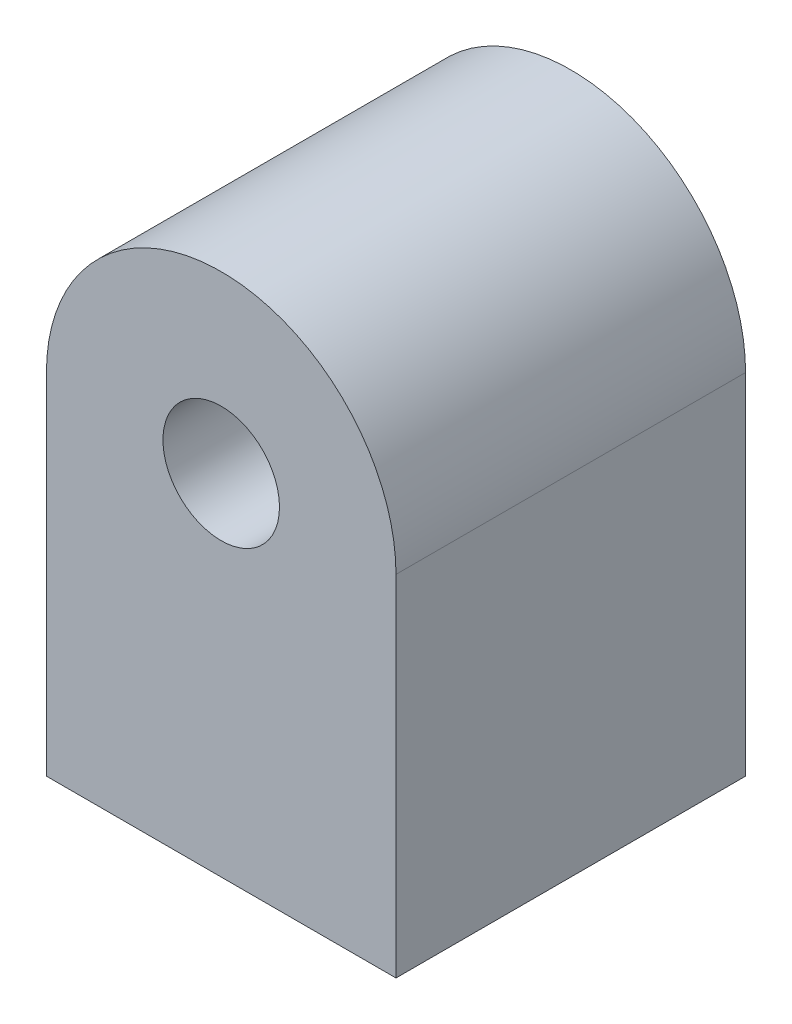
SolidWorks part; units mm, degrees
ref_plane "Front Plane" through (0, 0, 0) normal (0, 0, 1) x (1, 0, 0)
ref_plane "Top Plane" through (0, 0, 0) normal (0, 1, 0) x (1, 0, 0)
ref_plane "Right Plane" through (0, 0, 0) normal (1, 0, 0) x (0, 0, -1)
sketch "Sketch1" plane through (0, 0, 0) normal (0, 0, 1) x (1, 0, 0)
  line L0 (0, 0) -> (60, 0)
  line L1 (60, 0) -> (60, 60)
  line L2 (0, 60) -> (0, 0)
  arc A0 (60, 60) -> (0, 60) centre (30, 60) ccw
  circle A1 centre (30, 60) radius 10
  dimension "D3" = 20
  dimension "D1" = 60
  dimension "D2" = 60
extrude "Boss-Extrude1" add sketch "Sketch1" along normal blind 60
ref_plane "Plane1" through (0, 0, 30) normal (0, 0, 1) x (1, 0, 0)
sketch "Sketch4" plane through (0, 0, 30) normal (0, 0, 1) x (1, 0, 0)
  line L0 (0, 0) -> (60, 0) construction
  line L1 (30, 30) -> (30, -10)
  arc A0 (30, -10) -> (30, 30) centre (30, 10) ccw
  point P5 (30, 0)
  dimension "D1" = 40
  dimension "D2" = 10
revolve "Cut-Revolve1" cut sketch "Sketch4" angle 360 about L1
